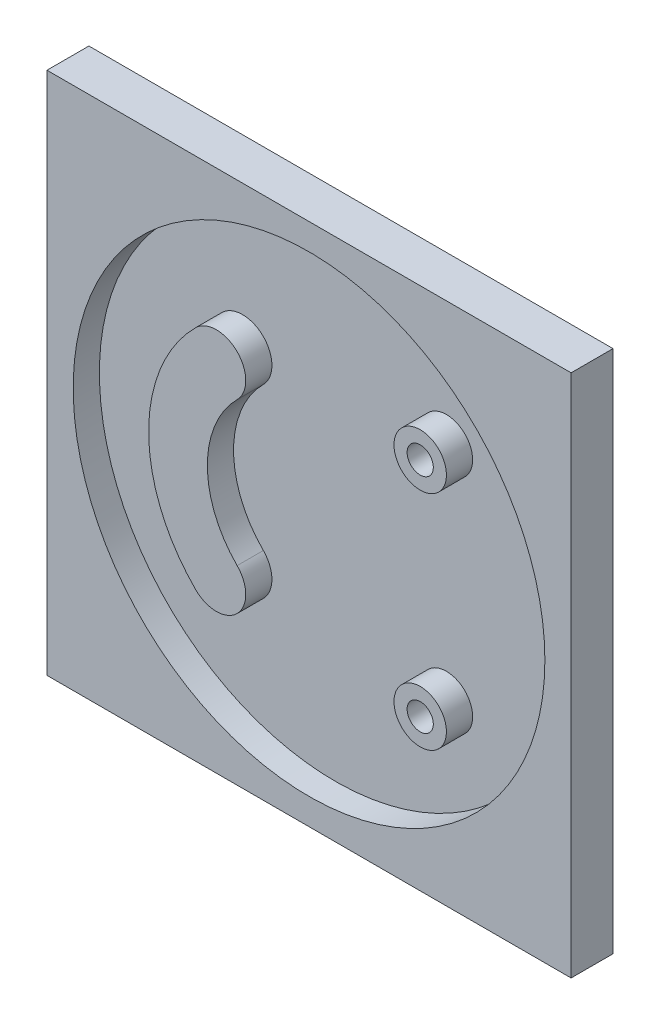
SolidWorks part; units mm, degrees
material "6061-T6 (SS)"
ref_plane "X-Y Datum" through (0, 0, 0) normal (0, 0, 1) x (1, 0, 0)
ref_plane "X-Z Datum" through (0, 0, 0) normal (0, 1, 0) x (1, 0, 0)
ref_plane "Y-Z Datum" through (0, 0, 0) normal (1, 0, 0) x (0, 0, -1)
sketch "Sketch1" plane through (0, 0, 0) normal (0, 0, 1) x (1, 0, 0)
  line L0 (127, 63.5) -> (0, 63.5) construction
  line L1 (0, 0) -> (127, 0)
  line L2 (0, 0) -> (0, 127)
  line L3 (0, 127) -> (127, 127)
  line L4 (127, 0) -> (127, 127)
  line L5 (127, 127) -> (63.5, 63.5) construction
  line L6 (63.5, 63.5) -> (127, 0) construction
  line L7 (63.5, 63.5) -> (0, 0) construction
  line L8 (63.5, 63.5) -> (0, 127) construction
  line L9 (90.4408, 90.4408) -> (90.4408, 36.5592) construction
  circle A0 centre (90.4408, 90.4408) radius 6.35
  circle A1 centre (90.4408, 36.5592) radius 6.35
  arc A2 (41.0494, 85.9506) -> (41.0494, 41.0494) centre (63.5, 63.5) ccw construction
  arc A3 (36.0204, 90.9796) -> (36.0204, 36.0204) centre (63.5, 63.5) ccw
  arc A4 (46.0783, 80.9217) -> (46.0783, 46.0783) centre (63.5, 63.5) ccw
  arc A5 (46.0783, 80.9217) -> (36.0204, 90.9796) centre (41.0494, 85.9506) ccw
  arc A6 (36.0204, 36.0204) -> (46.0783, 46.0783) centre (41.0494, 41.0494) ccw
  point P15 (31.75, 63.5)
  point P20 (0, 0)
  dimension "D3" = 12.7
  dimension "D4" = 12.7
  dimension "D8" = 7.112
  dimension "D1" = 127
  dimension "D2" = 127
  dimension "D5" = 38.1
  dimension "D6" = 38.1
  dimension "D7" = 53.8815
  dimension "D9" = 31.75
  dimension "D10" = 0
extrude "Boss-Extrude1" add sketch "Sketch1" along normal blind 10.16
sketch "Sketch3" plane through (0, 0, 10.16) normal (0, 0, 1) x (1, 0, 0)
  line L0 (0, 0) -> (127, 127) construction
  circle A0 centre (63.5, 63.5) radius 57.15
  dimension "D1" = 114.3
extrude "Cut-Extrude1" cut sketch "Sketch3" against normal blind 6.35
sketch "Sketch4" plane through (0, 0, 3.81) normal (0, 0, 1) x (1, 0, 0)
  circle A0 centre (90.4408, 36.5592) radius 6.35 construction
  circle A1 centre (90.4408, 90.4408) radius 6.35 construction
  circle A2 centre (90.4408, 36.5592) radius 6.35
  circle A3 centre (90.4408, 90.4408) radius 6.35
  arc A4 (46.0783, 80.9217) -> (46.0783, 46.0783) centre (63.5, 63.5) ccw
  arc A5 (46.0783, 80.9217) -> (36.0204, 90.9796) centre (41.0494, 85.9506) ccw
  arc A6 (36.0204, 90.9796) -> (36.0204, 36.0204) centre (63.5, 63.5) ccw
  arc A7 (36.0204, 36.0204) -> (46.0783, 46.0783) centre (41.0494, 41.0494) ccw
  arc A8 (46.0783, 80.9217) -> (46.0783, 46.0783) centre (63.5, 63.5) ccw
  arc A9 (46.0783, 80.9217) -> (36.0204, 90.9796) centre (41.0494, 85.9506) ccw
  arc A10 (36.0204, 90.9796) -> (36.0204, 36.0204) centre (63.5, 63.5) ccw
  arc A11 (36.0204, 36.0204) -> (46.0783, 46.0783) centre (41.0494, 41.0494) ccw
  dimension "D1" = 0
extrude "Boss-Extrude2" add sketch "Sketch4" along normal up to surface and the other way up to surface up to face at (120.65, 63.5, 10.16) other way up to face at (96.7908, 90.4408, 0)
sketch "Sketch5" plane through (0, 0, 10.16) normal (0, 0, 1) x (1, 0, 0)
  circle A0 centre (90.4408, 90.4408) radius 3.175
  circle A1 centre (90.4408, 36.5592) radius 3.175
  dimension "D1" = 6.35
  dimension "D2" = 6.35
extrude "Cut-Extrude2" cut sketch "Sketch5" against normal through all
